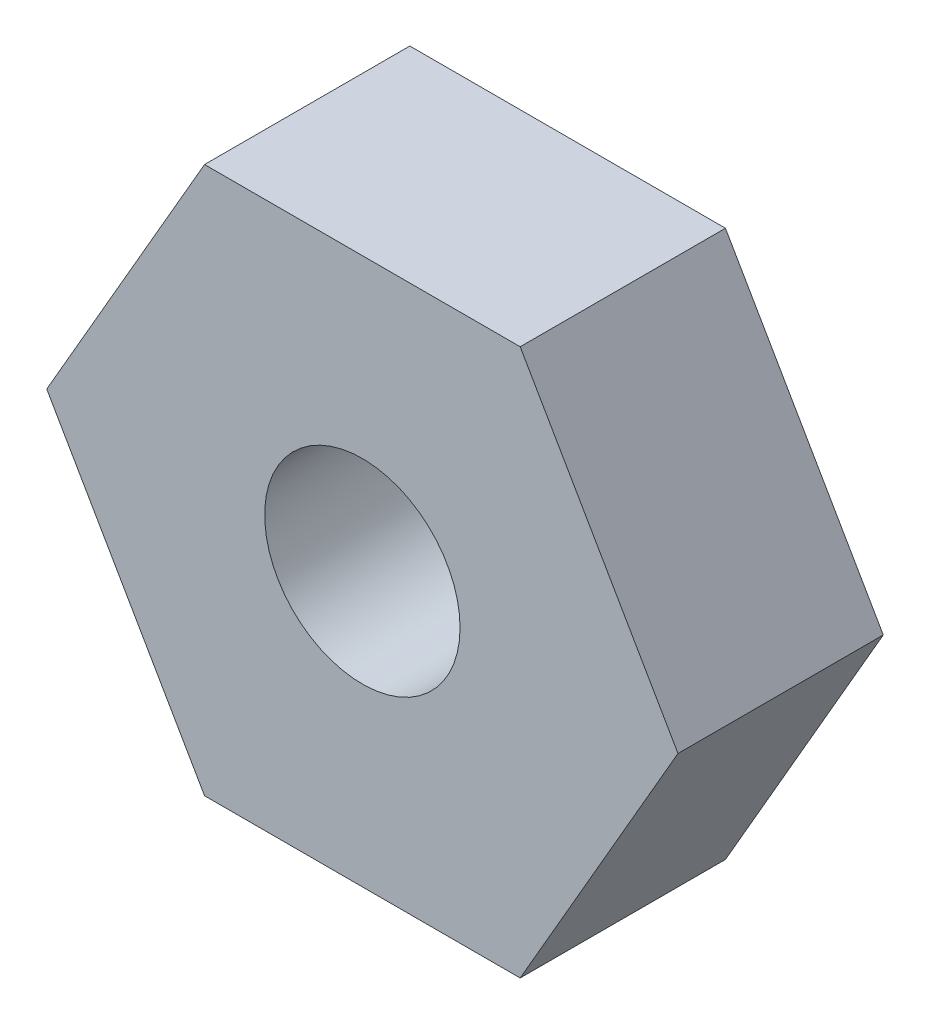
SolidWorks part; units mm, degrees
ref_plane "Front Plane" through (0, 0, 0) normal (0, 0, 1) x (1, 0, 0)
ref_plane "Top Plane" through (0, 0, 0) normal (0, 1, 0) x (1, 0, 0)
ref_plane "Right Plane" through (0, 0, 0) normal (1, 0, 0) x (0, 0, -1)
sketch "Sketch1" plane through (0, 0, 0) normal (0, 0, 1) x (1, 0, 0)
  line L1 (3.6515, 0) -> (1.8258, 3.1623)
  line L2 (1.8258, 3.1623) -> (-1.8258, 3.1623)
  line L3 (-1.8258, 3.1623) -> (-3.6515, 0)
  line L4 (-3.6515, 0) -> (-1.8258, -3.1623)
  line L5 (-1.8258, -3.1623) -> (1.8258, -3.1623)
  line L6 (1.8258, -3.1623) -> (3.6515, 0)
  circle A0 centre (0, 0) radius 3.1623 construction
  dimension "D1" = 6.3246
extrude "Boss-Extrude1" add sketch "Sketch1" along normal blind 2.3749
sketch "Sketch2" plane through (0, 0, 2.3749) normal (0, 0, 1) x (1, 0, 0)
  circle A0 centre (0, 0) radius 1.1303
  dimension "D1" = 2.2606
extrude "Cut-Extrude1" cut sketch "Sketch2" against normal up to surface (2.3749 mm away) up to face at (0, 0, 0)
